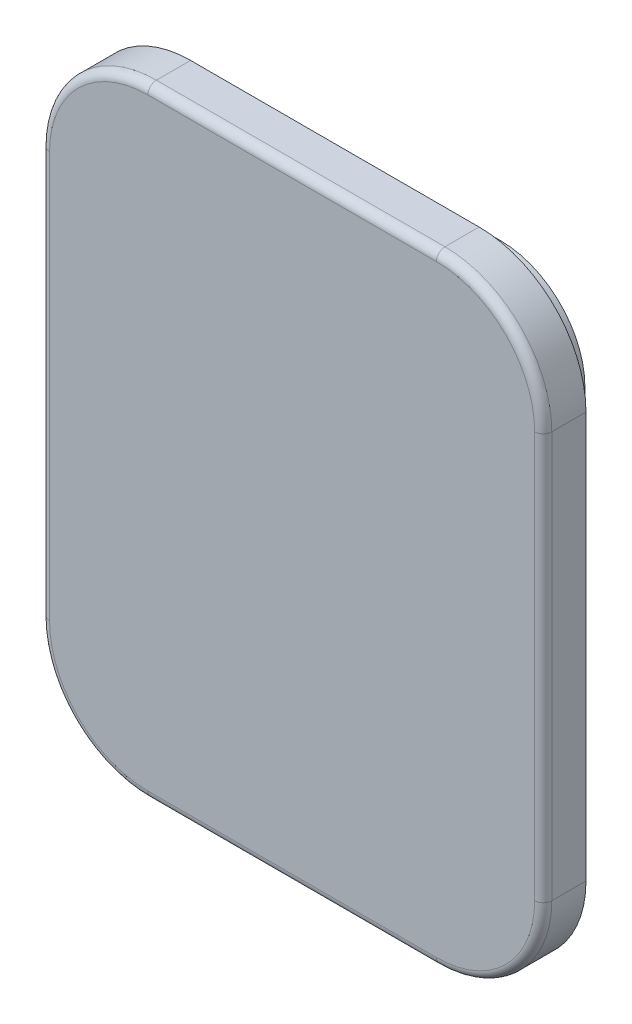
SolidWorks part; units mm, degrees
ref_plane "前视基准面" through (0, 0, 0) normal (0, 0, 1) x (1, 0, 0)
ref_plane "上视基准面" through (0, 0, 0) normal (0, 1, 0) x (1, 0, 0)
ref_plane "右视基准面" through (0, 0, 0) normal (1, 0, 0) x (0, 0, -1)
sketch "草图1" plane through (0, 0, 0) normal (0, 0, 1) x (1, 0, 0)
  line L0 (-13.5, 26.9) -> (13.5, 26.9)
  line L1 (21.4, 19) -> (21.4, -19)
  line L2 (13.5, -26.9) -> (-13.5, -26.9)
  line L3 (-21.4, -19) -> (-21.4, 19)
  arc A0 (13.5, 26.9) -> (21.4, 19) centre (13.5, 19) cw
  arc A1 (21.4, -19) -> (13.5, -26.9) centre (13.5, -19) cw
  arc A2 (-13.5, -26.9) -> (-21.4, -19) centre (-13.5, -19) cw
  arc A3 (-21.4, 19) -> (-13.5, 26.9) centre (-13.5, 19) cw
extrude "Lower_mating_lip_outer_2mm_overlap" add sketch "草图1" along normal blind 2
sketch "草图2" plane through (0, 0, 0) normal (0, 0, 1) x (1, 0, 0)
  line L0 (-12.6, 24.9) -> (12.6, 24.9)
  line L1 (19.4, 18.1) -> (19.4, -18.1)
  line L2 (12.6, -24.9) -> (-12.6, -24.9)
  line L3 (-19.4, -18.1) -> (-19.4, 18.1)
  arc A0 (12.6, 24.9) -> (19.4, 18.1) centre (12.6, 18.1) cw
  arc A1 (19.4, -18.1) -> (12.6, -24.9) centre (12.6, -18.1) cw
  arc A2 (-12.6, -24.9) -> (-19.4, -18.1) centre (-12.6, -18.1) cw
  arc A3 (-19.4, 18.1) -> (-12.6, 24.9) centre (-12.6, 18.1) cw
extrude "Lower_mating_lip_inner_clearance" cut sketch "草图2" along normal blind 2.3
ref_plane "Lower_visible_base_start_plane_2mm" through (0, 0, 2) normal (0, 0, 1) x (1, 0, 0)
sketch "草图3" plane through (0, 0, 2) normal (0, 0, 1) x (1, 0, 0)
  line L0 (-13.5, 29) -> (13.5, 29)
  line L1 (23.5, 19) -> (23.5, -19)
  line L2 (13.5, -29) -> (-13.5, -29)
  line L3 (-23.5, -19) -> (-23.5, 19)
  arc A0 (13.5, 29) -> (23.5, 19) centre (13.5, 19) cw
  arc A1 (23.5, -19) -> (13.5, -29) centre (13.5, -19) cw
  arc A2 (-13.5, -29) -> (-23.5, -19) centre (-13.5, -19) cw
  arc A3 (-23.5, 19) -> (-13.5, 29) centre (-13.5, 19) cw
extrude "Lower_visible_base_4mm" add sketch "草图3" along normal blind 4
fillet "Lower_bottom_edge_soft_fillet_r0_8" radius 0.8 8 edges at (0, 29, 6) (20.5711, 26.0711, 6) (23.5, 0, 6) (20.5711, -26.0711, 6) (0, -29, 6) (-20.5711, -26.0711, 6) (-23.5, 0, 6) (-20.5711, 26.0711, 6)
sketch "草图4" plane through (0, 0, 0) normal (0, 0, 1) x (1, 0, 0)
  line L0 (-12.5, -22.7) -> (-3, -22.7)
  line L1 (-3, -25.7) -> (-12.5, -25.7)
  arc A0 (-3, -22.7) -> (-3, -25.7) centre (-3, -24.2) cw
  arc A1 (-12.5, -25.7) -> (-12.5, -22.7) centre (-12.5, -24.2) cw
extrude "Lower_lanyard_left_window_12_5x3_v5" [suppressed] cut sketch "草图4" along normal blind 6.5
sketch "草图5" plane through (0, 0, 0) normal (0, 0, 1) x (1, 0, 0)
  line L0 (3, -22.7) -> (12.5, -22.7)
  line L1 (12.5, -25.7) -> (3, -25.7)
  arc A0 (12.5, -22.7) -> (12.5, -25.7) centre (12.5, -24.2) cw
  arc A1 (3, -25.7) -> (3, -22.7) centre (3, -24.2) cw
extrude "Lower_lanyard_right_window_12_5x3_v5" [suppressed] cut sketch "草图5" along normal blind 6.5
ref_plane "Lower_USB_C_right_side_lip_clearance_at_PCB_USB1_start_plane" through (0, 0, 0) normal (0, 0, 1) x (1, 0, 0)
sketch "草图6" plane through (0, 0, 0) normal (0, 0, 1) x (1, 0, 0)
  line L0 (18.2, 13.5046) -> (20.2, 13.5046)
  line L1 (21.4, 12.3046) -> (21.4, 5.7046)
  line L2 (20.2, 4.5046) -> (18.2, 4.5046)
  line L3 (17, 5.7046) -> (17, 12.3046)
  arc A0 (20.2, 13.5046) -> (21.4, 12.3046) centre (20.2, 12.3046) cw
  arc A1 (21.4, 5.7046) -> (20.2, 4.5046) centre (20.2, 5.7046) cw
  arc A2 (18.2, 4.5046) -> (17, 5.7046) centre (18.2, 5.7046) cw
  arc A3 (17, 12.3046) -> (18.2, 13.5046) centre (18.2, 12.3046) cw
extrude "Lower_USB_C_right_side_lip_clearance_at_PCB_USB1" cut sketch "草图6" along normal blind 1.3
sketch "草图7" plane through (0, 0, 0) normal (0, 0, 1) x (1, 0, 0)
  circle A0 centre (16.2727, 17.2937) radius 2.1
extrude "Lower_PCB1_locating_1_right_top_post_base_pad_d4_2_h0_8" add sketch "草图7" along normal blind 0.8
sketch "草图8" plane through (0, 0, 0) normal (0, 0, 1) x (1, 0, 0)
  circle A0 centre (16.2727, 17.2937) radius 1.3
extrude "Lower_PCB1_locating_1_right_top_solid_post_d2_6_h2_5" add sketch "草图8" along normal blind 2.5
fillet "Lower_PCB1_locating_1_right_top_solid_post_tip_fillet_r0_2" radius 0.2 1 edges at (18.3727, 17.2937, 0)
sketch "草图9" plane through (0, 0, 0) normal (0, 0, 1) x (1, 0, 0)
  circle A0 centre (16.1291, -17.4727) radius 2.1
extrude "Lower_PCB1_locating_2_right_bottom_post_base_pad_d4_2_h0_8" add sketch "草图9" along normal blind 0.8
sketch "草图10" plane through (0, 0, 0) normal (0, 0, 1) x (1, 0, 0)
  circle A0 centre (16.1291, -17.4727) radius 1.3
extrude "Lower_PCB1_locating_2_right_bottom_solid_post_d2_6_h2_5" add sketch "草图10" along normal blind 2.5
fillet "Lower_PCB1_locating_2_right_bottom_solid_post_tip_fillet_r0_2" radius 0.2 1 edges at (18.2291, -17.4727, 0)
sketch "草图11" plane through (0, 0, 0) normal (0, 0, 1) x (1, 0, 0)
  circle A0 centre (-16.5978, 17.4909) radius 2.1
extrude "Lower_PCB1_locating_3_left_top_post_base_pad_d4_2_h0_8" add sketch "草图11" along normal blind 0.8
sketch "草图12" plane through (0, 0, 0) normal (0, 0, 1) x (1, 0, 0)
  circle A0 centre (-16.5978, 17.4909) radius 1.3
extrude "Lower_PCB1_locating_3_left_top_solid_post_d2_6_h2_5" add sketch "草图12" along normal blind 2.5
fillet "Lower_PCB1_locating_3_left_top_solid_post_tip_fillet_r0_2" radius 0.2 1 edges at (-14.4978, 17.4909, 0)
sketch "草图13" plane through (0, 0, 0) normal (0, 0, 1) x (1, 0, 0)
  line L1 (-21.5, -20.5) -> (21.5, -20.5)
  line L2 (-21.5, -20.5) -> (-21.5, 21.5)
  line L3 (-21.5, 21.5) -> (21.5, 21.5)
  line L4 (21.5, -20.5) -> (21.5, 21.5)
  line L5 (-21.5, -20.5) -> (21.5, 21.5) construction
  line L6 (-21.5, 21.5) -> (21.5, -20.5) construction
  line L7 (-20, -20.5) -> (20, -20.5)
  line L8 (-20, -20.5) -> (-20, 16.5)
  line L9 (-20, 16.5) -> (20, 16.5)
  line L10 (20, -20.5) -> (20, 16.5)
  line L11 (-20, -20.5) -> (20, 16.5) construction
  line L12 (-20, 16.5) -> (20, -20.5) construction
  point P0 (0, -2)
sketch "草图14" plane through (0, 0, 0) normal (0, 0, 1) x (1, 0, 0)
  line L0 (-12.5, -25) -> (-3, -25)
  line L1 (-3, -28) -> (-12.5, -28)
  arc A0 (-3, -25) -> (-3, -28) centre (-3, -26.5) cw
  arc A1 (-12.5, -28) -> (-12.5, -25) centre (-12.5, -26.5) cw
extrude "Lower_lanyard_wet_zone_left_outer_window_v7_lip1mm" cut sketch "草图14" along normal blind 1.45
sketch "草图15" plane through (0, 0, 0) normal (0, 0, 1) x (1, 0, 0)
  line L0 (3, -25) -> (12.5, -25)
  line L1 (12.5, -28) -> (3, -28)
  arc A0 (12.5, -25) -> (12.5, -28) centre (12.5, -26.5) cw
  arc A1 (3, -28) -> (3, -25) centre (3, -26.5) cw
extrude "Lower_lanyard_wet_zone_right_outer_window_v7_lip1mm" cut sketch "草图15" along normal blind 1.45
sketch "草图16" plane through (0, 0, 0) normal (0, 0, 1) x (1, 0, 0)
  line L1 (-15.5, -24.25) -> (15.5, -24.25)
  line L2 (-15.5, -24.25) -> (-15.5, -23.55)
  line L3 (-15.5, -23.55) -> (15.5, -23.55)
  line L4 (15.5, -24.25) -> (15.5, -23.55)
  line L5 (-15.5, -24.25) -> (15.5, -23.55) construction
  line L6 (-15.5, -23.55) -> (15.5, -24.25) construction
extrude "Lower_lanyard_dry_zone_seal_rib_top_v7" add sketch "草图16" along normal blind 1.6 separate body
sketch "草图17" plane through (0, 0, 0) normal (0, 0, 1) x (1, 0, 0)
  line L1 (-15.85, -28.6) -> (-15.15, -28.6)
  line L2 (-15.85, -28.6) -> (-15.85, -24.4)
  line L3 (-15.85, -24.4) -> (-15.15, -24.4)
  line L4 (-15.15, -28.6) -> (-15.15, -24.4)
  line L5 (-15.85, -28.6) -> (-15.15, -24.4) construction
  line L6 (-15.85, -24.4) -> (-15.15, -28.6) construction
extrude "Lower_lanyard_dry_zone_seal_rib_left_v7" add sketch "草图17" along normal blind 1.6 separate body
sketch "草图18" plane through (0, 0, 0) normal (0, 0, 1) x (1, 0, 0)
  line L1 (15.15, -28.6) -> (15.85, -28.6)
  line L2 (15.15, -28.6) -> (15.15, -24.4)
  line L3 (15.15, -24.4) -> (15.85, -24.4)
  line L4 (15.85, -28.6) -> (15.85, -24.4)
  line L5 (15.15, -28.6) -> (15.85, -24.4) construction
  line L6 (15.15, -24.4) -> (15.85, -28.6) construction
extrude "Lower_lanyard_dry_zone_seal_rib_right_v7" add sketch "草图18" along normal blind 1.6 separate body
sketch "草图19"
sketch "草图20"
sketch "草图21"
